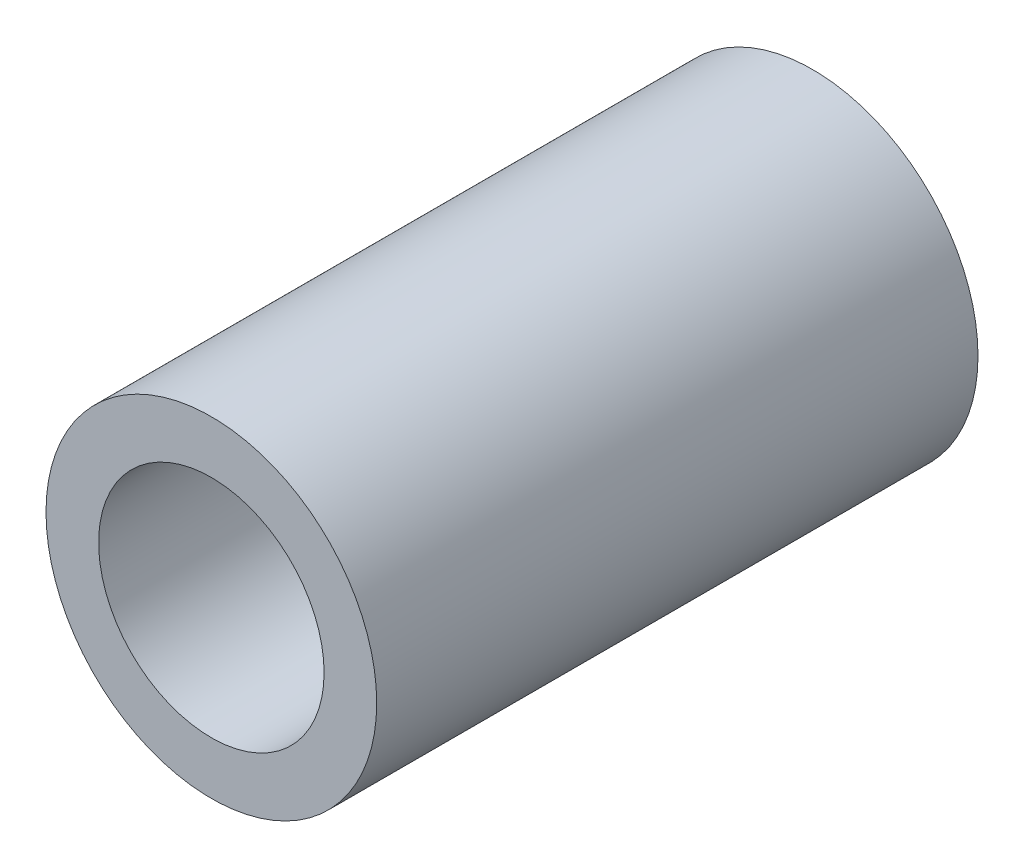
SolidWorks part; units mm, degrees
ref_plane "Plan de face" through (0, 0, 0) normal (0, 0, 1) x (1, 0, 0)
ref_plane "Plan de dessus" through (0, 0, 0) normal (0, 1, 0) x (1, 0, 0)
ref_plane "Plan de droite" through (0, 0, 0) normal (1, 0, 0) x (0, 0, -1)
sketch "Esquisse1" plane through (0, 0, 0) normal (0, 0, 1) x (1, 0, 0)
  circle A0 centre (0, 0) radius 1.5
  circle A1 centre (0, 0) radius 2.2
  dimension "D1" = 3
  dimension "D2" = 0.7
extrude "Boss.-Extru.1" add sketch "Esquisse1" along normal blind 8
